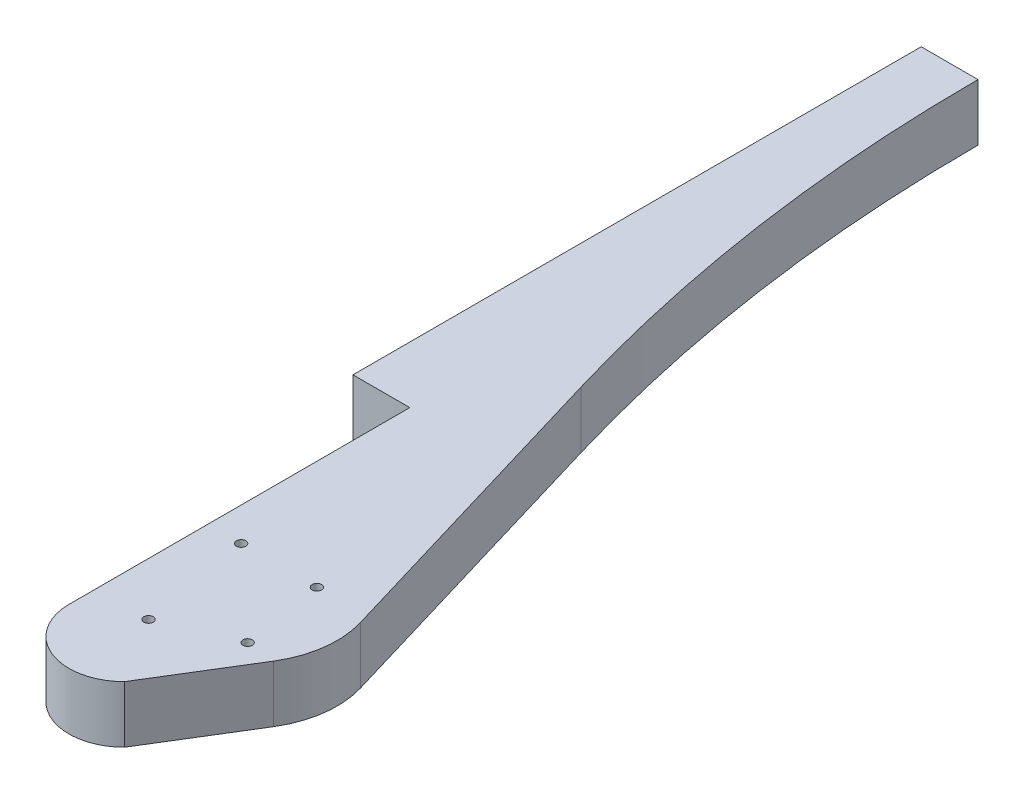
SolidWorks part; units mm, degrees
material "Pine"
ref_plane "Front Plane" through (0, 0, 0) normal (0, 0, 1) x (1, 0, 0)
ref_plane "Top Plane" through (0, 0, 0) normal (0, 1, 0) x (1, 0, 0)
ref_plane "Right Plane" through (0, 0, 0) normal (1, 0, 0) x (0, 0, -1)
sketch "Sketch1" plane through (0, 0, 0) normal (0, 1, 0) x (1, 0, 0)
  line L12 (0, 304.8) -> (0, 0) construction
  line L23 (31.75, -13.0735) -> (50.7652, 17.8819)
  line L24 (54.1393, 43.5679) -> (22.7226, 148.99)
  line L27 (0, 0) -> (31.75, -13.0735) construction
  line L28 (-19.05, 114.3) -> (0, 114.3)
  line L29 (0, 304.8) -> (-19.05, 304.8)
  line L30 (0, 114.3) -> (0, 0)
  line L32 (-19.05, 304.8) -> (-19.05, 114.3)
  arc A14 (0, 0) -> (31.75, -13.0735) centre (18.5666, 0) ccw
  arc A15 (50.7652, 17.8819) -> (54.1393, 43.5679) centre (23.7117, 34.5003) ccw
  arc A16 (22.7226, 148.99) -> (0, 304.8) centre (545.5597, 304.8) cw
other "AlignGroup1" parameters "D5"=10.6777, "D2"=6.35, "D11"=87.1705, "D12"=33.4582, "D8"=31.75, "D9"=9.7381, "D13"=69.443, "D14"=18.5666, "D15"=145.5834, "D1"=112.3753, "D3"=95.7306, "D4"=21.8056, "D6"=224.7252, "D7"=76.8916, "D10"=53.7406
extrude "Boss-Extrude1" add sketch "Sketch1" along normal blind 19.05
ref_plane "Plane1" through (0, 0, 18.5666) normal (0, 0, 1) x (1, 0, 0)
hole_wizard "1/8 (0.125) Diameter Hole1" positions "Sketch2" profile "Sketch3" hole size "1/8" standard "ANSI Inch"
sketch "Sketch2" plane through (0, 0, 0) normal (0, -1, 0) x (-1, 0, 0)
  line L0 (9.525, 304.8) -> (9.525, 139.7) construction
  line L4 (0, 304.8) -> (0, 114.3) construction
  line L6 (19.05, 304.8) -> (19.05, 114.3) construction
  line L12 (19.05, 139.7) -> (-25.4911, 139.7) construction
  line L13 (-54.1393, 43.5679) -> (-22.7226, 148.99) construction
  line L15 (19.05, 114.3) -> (0, 114.3) construction
  line L16 (-18.5666, -18.5666) -> (-18.5666, 139.7) construction
  line L18 (0, 304.8) -> (19.05, 304.8) construction
  arc A0 (-31.75, -13.0735) -> (0, 0) centre (-18.5666, 0) ccw construction
  point P2 (-3.2206, 139.7)
  point P4 (-18.5666, 0)
  point P41 (-3.2206, 139.7)
  point P59 (9.525, 279.4)
  dimension "D1" = 25.4
  dimension "D2" = 25.4
sketch "Sketch3" plane through (3.2206, 0, -139.7) normal (1, 0, 0) x (0, 0, -1)
  line L0 (0, 0) -> (0, 12.0791)
  line L1 (0, 12.0791) -> (1.5875, 11.1252)
  line L2 (1.5875, 11.1252) -> (1.5875, 0)
  line L5 (1.5875, 0) -> (0, 0)
  line L10 (0, 12.0791) -> (-1.5875, 11.1252) construction
  line L11 (0, -6.35) -> (0, 107.95) construction
  dimension "Hole Dia." = 3.175
  dimension "Hole Depth" = 11.1252
  dimension "Drill Angle" = 118
sketch "Sketch4" plane through (0, 19.05, 0) normal (0, 1, 0) x (1, 0, 0)
  line L0 (0, 114.3) -> (0, 0) construction
  arc A0 (0, 0) -> (31.75, -13.0735) centre (18.5666, 0) ccw construction
  line B0 (0, 304.8) -> (0, 0)
  line B1 (31.75, -13.0735) -> (50.7652, 17.8819)
  line B2 (54.1393, 43.5679) -> (22.7226, 148.99)
  line B3 (58.6114, 41.8067) -> (58.6176, 54.5037)
  line B4 (58.6176, 54.5037) -> (52.2681, 54.5051)
  line B5 (52.2681, 54.5051) -> (52.262, 41.808)
  line B6 (55.6545, 25.0952) -> (60.6107, 13.4065)
  line B7 (60.6107, 13.4065) -> (66.4566, 15.8858)
  line B8 (66.4566, 15.8858) -> (61.5004, 27.5745)
  line B9 (7.8155, 41.8175) -> (7.8217, 54.5145)
  line B10 (7.8217, 54.5145) -> (1.4722, 54.5159)
  line B11 (1.4722, 54.5159) -> (1.466, 41.8188)
  arc B12 (50.7652, 17.8819) -> (54.1393, 43.5679) centre (23.7117, 34.5003) ccw
  ellipse B13 centre (95.0399, 41.7989) end of major axis (126.4756, 60.2118) minor radius 36.4199 (58.6114, 41.8067) -> (61.5004, 27.5745) ccw
  ellipse B14 centre (95.0399, 41.7989) end of major axis (58.1248, 20.1766) minor radius 42.7679 (52.262, 41.808) -> (55.6545, 25.0952) ccw
  ellipse B15 centre (95.0399, 41.7989) end of major axis (170.3098, 85.8869) minor radius 87.204 (7.8155, 41.8175) -> (14.7328, 7.74) ccw
  ellipse B16 centre (95.0399, 41.7989) end of major axis (175.789, 89.0963) minor radius 93.552 (1.466, 41.8188) -> (8.8869, 5.2607) ccw
  ellipse B17 centre (40.0695, 4.8661) end of major axis (63.4541, 14.7816) minor radius 0.631 (63.4532, 14.7834) -> (16.6857, -5.0512) ccw
  ellipse B18 centre (29.9645, 54.647) end of major axis (55.3645, 54.6347) minor radius 0.5489 (55.3625, 54.6416) -> (4.5666, 54.6525) ccw
sketch_block_instance "Joint 2 Mounting Geometry-1"
sketch_block "Joint 2 Mounting Geometry"
sketch "Sketch5" plane through (0, 19.05, 0) normal (0, 1, 0) x (1, 0, 0)
  line L4 (11.1782, 46.5763) -> (36.5782, 46.5709) construction
  line L5 (17.7079, 9.006) -> (41.038, 18.9005) construction
  line L6 (19.689, -3.9488) -> (60.6107, 13.4065) construction
  line L7 (7.8217, 54.5145) -> (52.2681, 54.5051) construction
  circle A0 centre (11.1782, 46.5763) radius 3.9688
  arc A2 (11.1782, 46.5763) -> (17.7079, 9.006) centre (95.0399, 41.7989) ccw construction
  arc A3 (36.5782, 46.5709) -> (41.038, 18.9005) centre (95.0399, 41.7989) ccw construction
  circle A4 centre (36.5782, 46.5709) radius 3.9687
  circle A5 centre (41.038, 18.9005) radius 3.9687
  circle A6 centre (17.7079, 9.006) radius 3.9688
  ellipse E0 centre (95.0399, 41.7989) end of major axis (58.1248, 20.1766) minor radius 42.7679 (52.262, 41.808) -> (55.6545, 25.0952) ccw construction
  ellipse E1 centre (95.0399, 41.7989) end of major axis (170.3098, 85.8869) minor radius 87.204 (7.8155, 41.8175) -> (14.7328, 7.74) ccw construction
  ellipse E3 centre (95.0399, 41.7989) end of major axis (170.3098, 85.8869) minor radius 87.204 (7.8155, 41.8175) -> (14.7328, 7.74) ccw construction
  ellipse E5 centre (95.0399, 41.7989) end of major axis (58.1248, 20.1766) minor radius 42.7679 (52.262, 41.808) -> (55.6545, 25.0952) ccw construction
  dimension "D4" = 15.875
  dimension "D5" = 7.9375
  dimension "D1" = 12.7
  dimension "D2" = 7.9375
  dimension "D3" = 25.4
hole_wizard "1/8 (0.125) Diameter Hole2" positions "Sketch8" profile "Sketch9" hole size "1/8" standard "ANSI Inch" end condition through all
sketch "Sketch8" plane through (0, 19.05, 0) normal (0, 1, 0) x (1, 0, 0)
  point P0 (36.5782, 46.5709)
  point P3 (11.1782, 46.5763)
  point P6 (17.7079, 9.006)
  point P9 (41.038, 18.9005)
sketch "Sketch9" plane through (36.5782, 19.05, -46.5709) normal (1, 0, 0) x (0, 0, 1)
  line L0 (0, 0) -> (0, 19.05)
  line L1 (0, 19.05) -> (1.5875, 19.05)
  line L2 (1.5875, 19.05) -> (1.5875, 0)
  line L5 (1.5875, 0) -> (0, 0)
  line L11 (0, -6.35) -> (0, 107.95) construction
  dimension "Thru Hole Dia." = 3.175
  dimension "Thru Hole Depth" = 19.05
